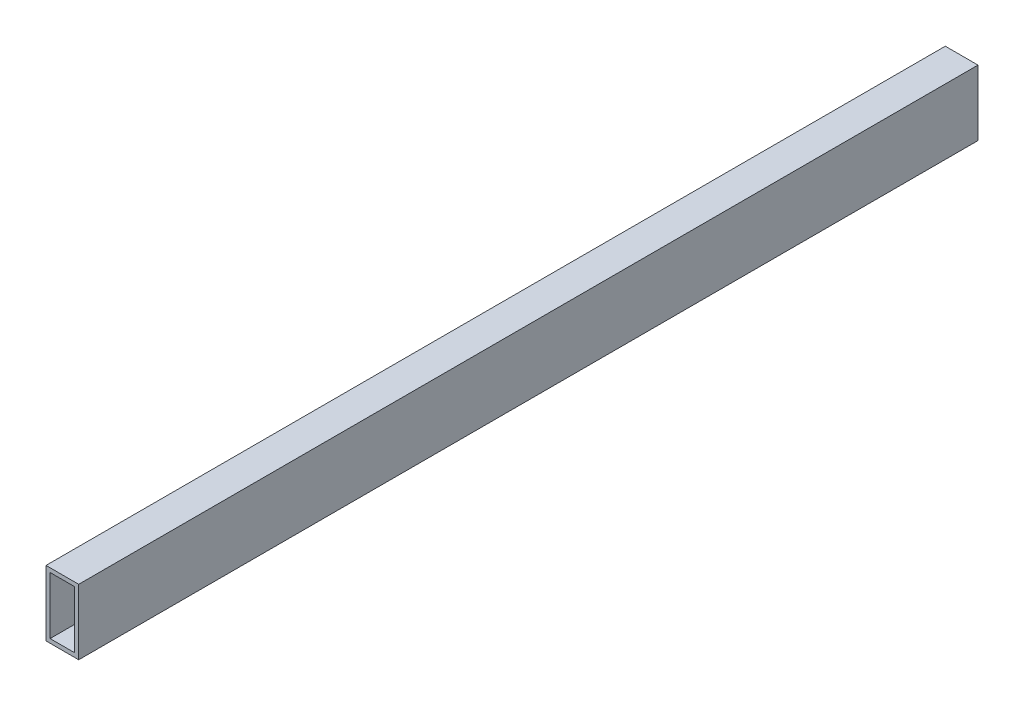
SolidWorks part; units mm, degrees
material "6061-T4 (SS)"
ref_plane "Front Plane" through (0, 0, 0) normal (0, 0, 1) x (1, 0, 0)
ref_plane "Top Plane" through (0, 0, 0) normal (0, 1, 0) x (1, 0, 0)
ref_plane "Right Plane" through (0, 0, 0) normal (1, 0, 0) x (0, 0, -1)
sketch "Sketch1" plane through (0, 0, 0) normal (0, 0, 1) x (1, 0, 0)
  line L0 (-9.525, 22.225) -> (9.525, 22.225)
  line L1 (-12.7, 25.4) -> (12.7, 25.4)
  line L2 (-12.7, 25.4) -> (-12.7, -25.4)
  line L3 (-12.7, -25.4) -> (12.7, -25.4)
  line L4 (12.7, 25.4) -> (12.7, -25.4)
  line L5 (-12.7, 25.4) -> (12.7, -25.4) construction
  line L6 (-12.7, -25.4) -> (12.7, 25.4) construction
  line L7 (9.525, 22.225) -> (9.525, -22.225)
  line L8 (-9.525, -22.225) -> (9.525, -22.225)
  line L9 (-9.525, 22.225) -> (-9.525, -22.225)
  point P0 (0, 0)
  dimension "D1" = 50.8
  dimension "D2" = 25.4
  dimension "D3" = 3.175
extrude "Boss-Extrude1" add sketch "Sketch1" along normal mid plane 698.5
